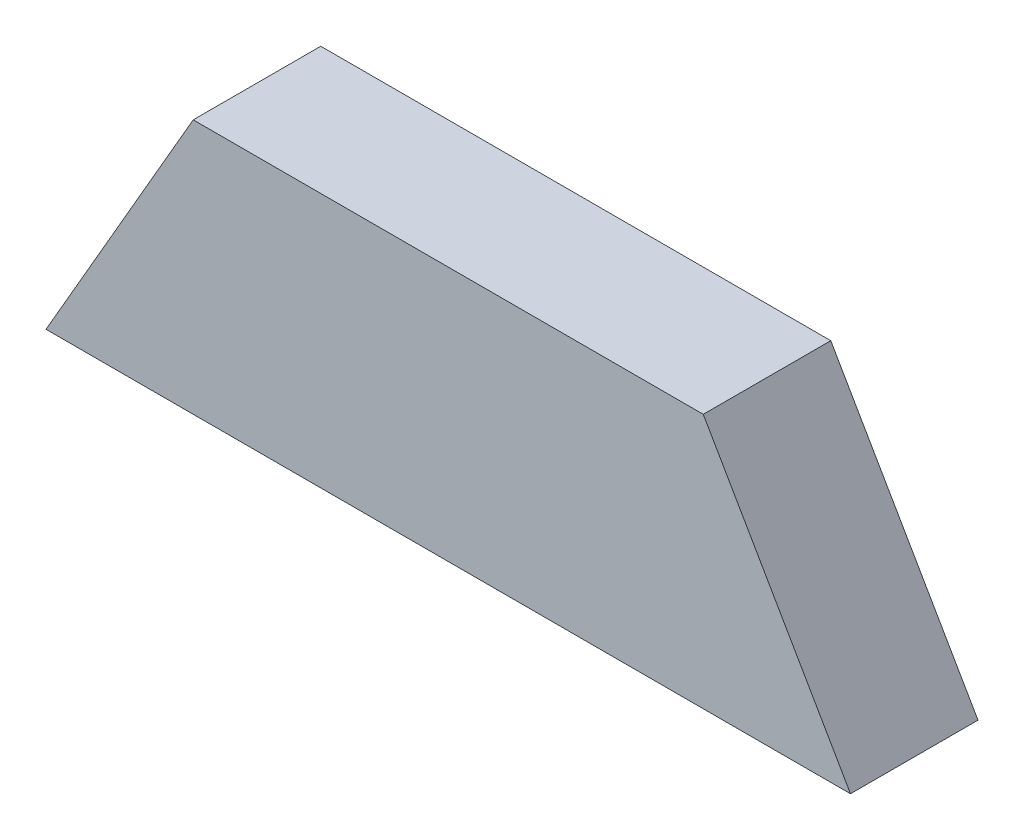
SolidWorks part; units mm, degrees
ref_plane "Front Plane" through (0, 0, 0) normal (0, 0, 1) x (1, 0, 0)
ref_plane "Top Plane" through (0, 0, 0) normal (0, 1, 0) x (1, 0, 0)
ref_plane "Right Plane" through (0, 0, 0) normal (1, 0, 0) x (0, 0, -1)
sketch "Sketch1" plane through (0, 0, 0) normal (0, 0, 1) x (1, 0, 0)
  line L0 (-6.35, 0) -> (6.35, 0)
  line L1 (6.35, 0) -> (10.0162, -6.35)
  line L2 (10.0162, -6.35) -> (-10.0162, -6.35)
  line L3 (-10.0162, -6.35) -> (-6.35, 0)
  dimension "D1" = 12.7
  dimension "D2" = 6.35
  dimension "D3" = 60
extrude "Boss-Extrude1" add sketch "Sketch1" along normal blind 3.175
